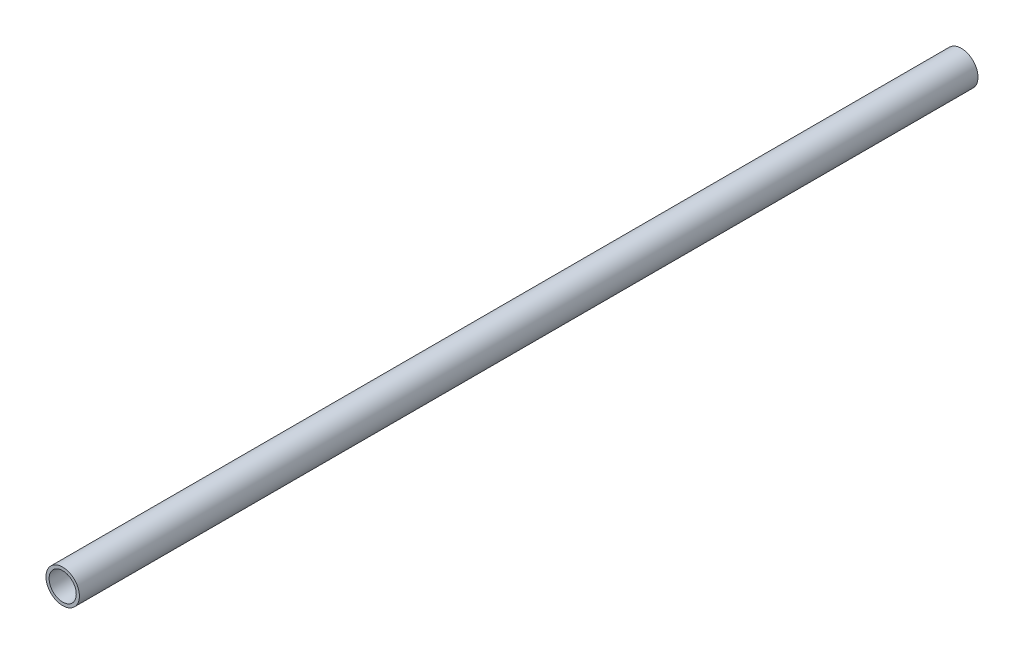
SolidWorks part; units mm, degrees
ref_plane "Alzado" through (0, 0, 0) normal (0, 0, 1) x (1, 0, 0)
ref_plane "Planta" through (0, 0, 0) normal (0, 1, 0) x (1, 0, 0)
ref_plane "Vista lateral" through (0, 0, 0) normal (1, 0, 0) x (0, 0, -1)
sketch "Croquis1" plane through (0, 0, 0) normal (0, 0, 1) x (1, 0, 0)
  circle A0 centre (0, 0) radius 16
  dimension "D1" = 32
extrude "Extruir1" add sketch "Croquis1" along normal mid plane 860
shell "Vaciado1" thickness 3
